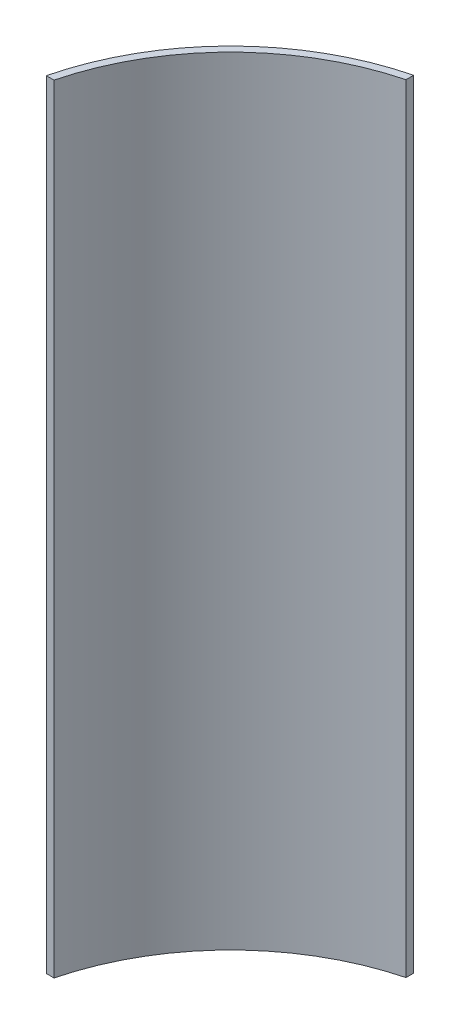
SolidWorks part; units mm, degrees
ref_plane "Front" through (0, 0, 0) normal (0, 0, 1) x (1, 0, 0)
ref_plane "Top" through (0, 0, 0) normal (0, 1, 0) x (1, 0, 0)
ref_plane "Right" through (0, 0, 0) normal (1, 0, 0) x (0, 0, -1)
sketch "Эскиз1" plane through (0, 0, 0) normal (0, 1, 0) x (1, 0, 0)
  line L1 (-39.3212, 9.7) -> (-38.0841, 9.7)
  line L2 (-9.8541, 38.0445) -> (-9.8541, 39.2829)
  arc A0 (-9.8541, 39.2829) -> (-39.3212, 9.7) centre (0, 0) ccw
  arc A1 (-9.8541, 38.0445) -> (-38.0841, 9.7) centre (0, 0) ccw
  dimension "D1" = 81
  dimension "D2" = 78.6
  dimension "D3" = 28.23
  dimension "D4" = 9.7
extrude "Бобышка-Вытянуть1" add sketch "Эскиз1" along normal blind 125
